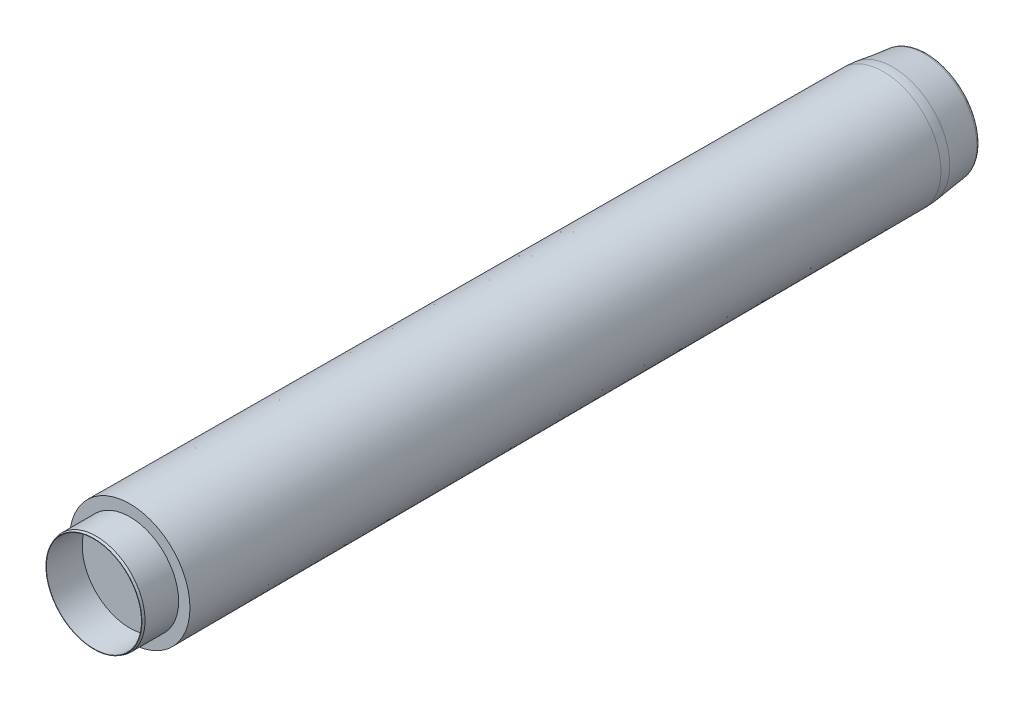
SolidWorks part; units mm, degrees
material "PVC 0.007 Plasticized"
ref_plane "Front Plane" through (0, 0, 0) normal (0, 0, 1) x (1, 0, 0)
ref_plane "Top Plane" through (0, 0, 0) normal (0, 1, 0) x (1, 0, 0)
ref_plane "Right Plane" through (0, 0, 0) normal (1, 0, 0) x (0, 0, -1)
sketch "Sketch1" plane through (0, 0, 0) normal (0, 0, 1) x (1, 0, 0)
  circle A0 centre (0, 0) radius 6.25
  circle A1 centre (0, 0) radius 7.7
  dimension "D1" = 12.5
  dimension "D2" = 15.4
extrude "Boss-Extrude3" add sketch "Sketch1" against normal blind 102.14 draft 0.2 contours A1
sketch "Sketch3" plane through (0, 0, 0) normal (0, 0, 1) x (1, 0, 0)
  circle A0 centre (0, 0) radius 6.1
  circle A1 centre (0, 0) radius 6.25
  dimension "D1" = 12.5
  dimension "D2" = 12.2
extrude "Boss-Extrude4" add sketch "Sketch3" along normal blind 4.6
chamfer "Chamfer1" distance 0.6 distance2 5 1 edges at (7.3435, 0, -102.14)
fillet "Fillet1" radius 0.5 1 edges at (6.7435, 0, -102.14)
fillet "Fillet2" radius 10 1 edges at (7.3609, 0, -97.14)
chamfer "Chamfer2" distance 0.3 distance2 0.1 1 edges at (6.25, 0, 4.6)
